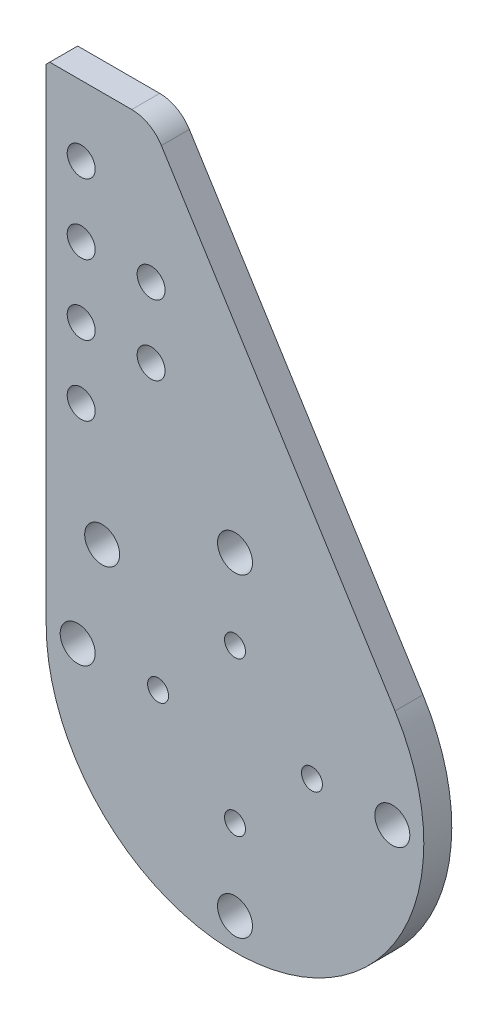
SolidWorks part; units mm, degrees
material "6061 合金"
ref_plane "前视基准面" through (0, 0, 0) normal (0, 0, 1) x (1, 0, 0)
ref_plane "上视基准面" through (0, 0, 0) normal (0, 1, 0) x (1, 0, 0)
ref_plane "右视基准面" through (0, 0, 0) normal (1, 0, 0) x (0, 0, -1)
sketch "草图1" plane through (0, 0, 0) normal (0, 0, 1) x (1, 0, 0)
  line L0 (0, 0) -> (0, 70) construction
  line L1 (-27, 0) -> (-27, 70)
  line L2 (-27, 70) -> (-12, 70)
  line L3 (-12, 70) -> (22.8794, 14.3365)
  line L4 (0, 0) -> (0, 35) construction
  line L5 (-22, 70) -> (-22, 60) construction
  line L6 (-22, 60) -> (-22, 50) construction
  line L7 (-22, 50) -> (-22, 30) construction
  line L8 (-22, 30) -> (-22, 20) construction
  line L9 (-22, 30) -> (-22, 14) construction
  line L10 (-22, 14) -> (-19, 14) construction
  arc A0 (-27, 0) -> (22.8794, 14.3365) centre (0, 0) ccw
  circle A1 centre (0, 0) radius 22.5 construction
  circle A2 centre (0, 22.5) radius 2.5
  circle A3 centre (22.5, 0) radius 2.5
  circle A4 centre (0, -22.5) radius 2.5
  circle A5 centre (-22.5, 0) radius 2.5
  circle A6 centre (-22, 60) radius 2
  circle A7 centre (-22, 50) radius 2
  circle A8 centre (-22, 30) radius 2
  circle A10 centre (0, 0) radius 18 construction
  circle A13 centre (-22, 40) radius 2
  circle A16 centre (-12, 50) radius 2
  circle A19 centre (0, 0) radius 11 construction
  circle A20 centre (0, 11) radius 1.5
  circle A21 centre (11, 0) radius 1.5
  circle A22 centre (0, -11) radius 1.5
  circle A23 centre (-11, 0) radius 1.5
  circle A24 centre (-12, 40) radius 2
  circle A25 centre (-19, 14) radius 2.5
  point P19 (0, 0)
  point P46 (0, 0)
  dimension "D1" = 4
  dimension "D4" = 27
  dimension "D8" = 4
  dimension "D10" = 10
  dimension "D2" = 10
  dimension "D3" = 70
  dimension "D5" = 10
  dimension "D6" = 20
  dimension "D7" = 10
  dimension "D9" = 5
extrude "凸台-拉伸1" add sketch "草图1" along normal blind 4
fillet "圆角1" radius 5 1 edges at (-12, 70, 2)
chamfer "倒角1" distance 0.5 angle 45 1 edges at (-27, 70, 2)
